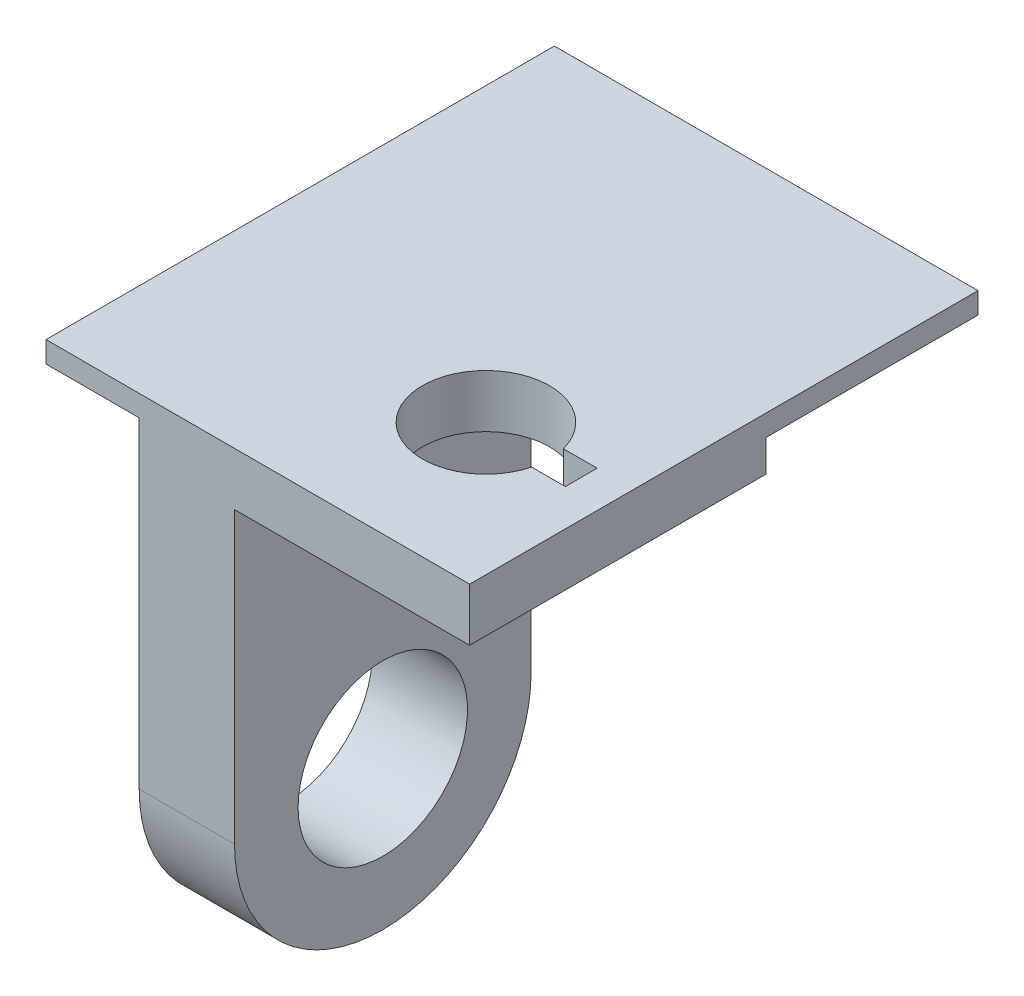
SolidWorks part; units mm, degrees
material "Acciaio al carbonio semplice"
ref_plane "Piano frontale" through (0, 0, 0) normal (0, 0, 1) x (1, 0, 0)
ref_plane "Piano superiore" through (0, 0, 0) normal (0, 1, 0) x (1, 0, 0)
ref_plane "Piano destro" through (0, 0, 0) normal (1, 0, 0) x (0, 0, -1)
sketch "Schizzo1" plane through (0, 0, 0) normal (1, 0, 0) x (0, 0, -1)
  line L0 (-826.3993, 0) -> (40493.5669, 0) construction
  line L1 (0, -826.3993) -> (0, 40493.5669) construction
  line L2 (-70, 0) -> (-70, 136.8)
  line L3 (-70, 136.8) -> (70, 136.8)
  line L4 (70, 136.8) -> (70, 0)
  circle A0 centre (0, 0) radius 40
  arc A1 (-70, 0) -> (70, 0) centre (0, 0) ccw
  dimension "D1" = 70
  dimension "D2" = 80
  dimension "D3" = 136.8
extrude "Estrusione-Estrusione1" add sketch "Schizzo1" along normal blind 45
sketch "Schizzo2" plane through (0, 136.8, 0) normal (0, 1, 0) x (1, 0, 0)
  line L0 (-1000, 0) -> (49000, 0) construction
  line L1 (93.7, -996.2442) -> (93.7, 49003.7558) construction
  line L6 (45, -70) -> (0, -70) construction
  line L7 (0, 70) -> (156, 70)
  line L8 (0, 70) -> (0, -70)
  line L9 (0, -70) -> (156, -70)
  line L10 (156, 70) -> (156, -70)
  circle A0 centre (93.7, 0) radius 30
  dimension "D1" = 93.7
  dimension "D2" = 156
  dimension "D3" = 60
extrude "Estrusione-Estrusione2" add sketch "Schizzo2" along normal blind 25
sketch "Schizzo5" plane through (0, 161.8, 0) normal (0, 1, 0) x (1, 0, 0)
  line L1 (0, -70) -> (-44, -70)
  line L2 (0, -70) -> (0, 70)
  line L3 (156, 170) -> (-44, 170)
  line L4 (-44, -70) -> (-44, 170)
  line L5 (-44, 170) -> (156, 170)
  line L6 (-44, 170) -> (-44, -70)
  line L7 (0, 70) -> (156, 70)
  line L8 (156, 170) -> (156, 70)
  line M8 (0, 70) -> (0, -70)
  line M11 (156, 70) -> (0, 70)
  dimension "D1" = 200
  dimension "D2" = 240
extrude "Estrusione-Estrusione4" add sketch "Schizzo5" against normal blind 10 contours L8 L3 L4 L1 M8 M11
sketch "Schizzo6" plane through (0, 161.8, 0) normal (0, 1, 0) x (1, 0, 0)
  line L0 (-906.3, 0) -> (49093.7, 0) construction
  line L2 (138.7, 7.5) -> (93.7, 7.5)
  line L3 (138.7, 7.5) -> (138.7, -7.5)
  line L4 (138.7, -7.5) -> (93.7, -7.5)
  line L5 (93.7, 7.5) -> (93.7, -7.5)
  line L6 (138.7, 7.5) -> (93.7, -7.5) construction
  line L7 (138.7, -7.5) -> (93.7, 7.5) construction
  circle A1 centre (93.7, 0) radius 30 construction
  circle A2 centre (93.7, 0) radius 30 construction
  point P0 (116.2, 0)
  dimension "D1" = 45
  dimension "D2" = 15
extrude "Taglio-Estrusione1" cut sketch "Schizzo6" against normal up to surface (25 mm away) up to face at (100.5, 136.8, 0)
